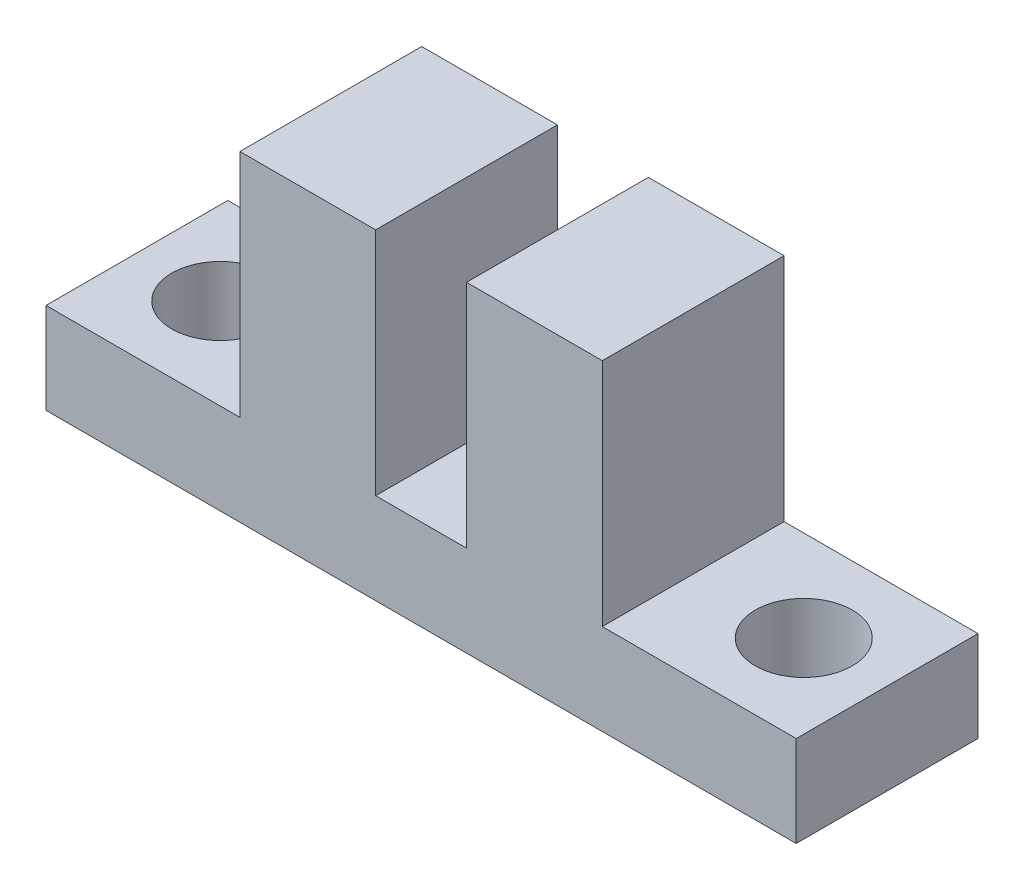
SolidWorks part; units mm, degrees
material "ABS"
ref_plane "Alzado" through (0, 0, 0) normal (0, 0, 1) x (1, 0, 0)
ref_plane "Planta" through (0, 0, 0) normal (0, 1, 0) x (1, 0, 0)
ref_plane "Vista lateral" through (0, 0, 0) normal (1, 0, 0) x (0, 0, -1)
sketch "Croquis1" plane through (0, 0, 0) normal (0, 0, 1) x (1, 0, 0)
  line L0 (-9.4676, 5.4982) -> (-4.9876, 5.4982)
  line L1 (-4.9876, 5.4982) -> (-4.9876, -2.1018)
  line L2 (-4.9876, -2.1018) -> (-1.9876, -2.1018)
  line L3 (-1.9876, -2.1018) -> (-1.9876, 5.4982)
  line L4 (-1.9876, 5.4982) -> (2.4924, 5.4982)
  line L5 (2.4924, 5.4982) -> (2.4924, -2.1018)
  line L6 (2.4924, -2.1018) -> (8.8924, -2.1018)
  line L7 (8.8924, -2.1018) -> (8.8924, -5.1018)
  line L8 (8.8924, -5.1018) -> (-15.8676, -5.1018)
  line L9 (-15.8676, -5.1018) -> (-15.8676, -2.1018)
  line L10 (-15.8676, -2.1018) -> (-9.4676, -2.1018)
  line L11 (-9.4676, -2.1018) -> (-9.4676, 5.4982)
  dimension "D1" = 4.48
  dimension "D2" = 7.6
  dimension "D3" = 3
  dimension "D4" = 6.4
  dimension "D5" = 3
extrude "Saliente-Extruir1" add sketch "Croquis1" along normal blind 6
sketch "Croquis2" plane through (0, -2.1018, 0) normal (0, 1, 0) x (1, 0, 0)
  line L0 (-3.4876, 0) -> (-3.4876, -6) construction
  line L1 (-1.9876, 0) -> (-4.9876, 0) construction
  line L2 (-1.9876, -6) -> (-4.9876, -6) construction
  line L3 (-15.8676, -3) -> (8.8924, -3) construction
  line L4 (-15.8676, -6) -> (-15.8676, 0) construction
  line L5 (8.8924, -6) -> (8.8924, 0) construction
  circle A0 centre (-13.1176, -3) radius 1.6
  circle A1 centre (6.1424, -3) radius 1.6
  point P14 (0, 0)
  dimension "D1" = 3.2
  dimension "D2" = 2.75
extrude "Cortar-Extruir1" cut sketch "Croquis2" against normal through all
